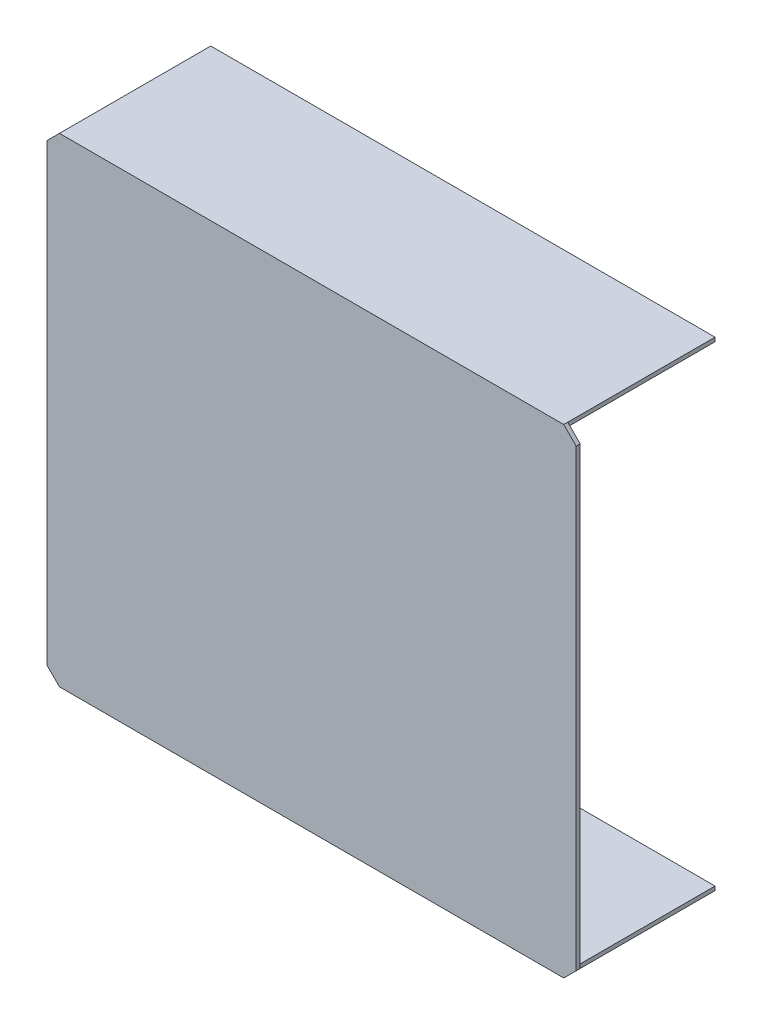
SolidWorks part; units mm, degrees
ref_plane "Front Plane" through (0, 0, 0) normal (0, 0, 1) x (1, 0, 0)
ref_plane "Top Plane" through (0, 0, 0) normal (0, 1, 0) x (1, 0, 0)
ref_plane "Right Plane" through (0, 0, 0) normal (1, 0, 0) x (0, 0, -1)
sketch "Sketch1" plane through (0, 0, 0) normal (0, 0, 1) x (1, 0, 0)
  line L0 (-101, -96) -> (101, -96)
  line L1 (101, -96) -> (106, -91)
  line L2 (106, -91) -> (106, 91)
  line L3 (106, 91) -> (101, 96)
  line L4 (101, 96) -> (-101, 96)
  line L5 (-101, 96) -> (-106, 91)
  line L6 (-106, 91) -> (-106, -91)
  line L7 (-106, -91) -> (-101, -96)
extrude "5052 sheet top panel" add sketch "Sketch1" along normal blind 1.6 from offset 86
sketch "Sketch2" plane through (0, 0, 0) normal (0, 0, 1) x (1, 0, 0)
  line L0 (-101, 94.4) -> (101, 94.4)
  line L1 (101, 94.4) -> (101, 96)
  line L2 (101, 96) -> (-101, 96)
  line L3 (-101, 96) -> (-101, 94.4)
  line L4 (-101, -96) -> (101, -96)
  line L5 (101, -96) -> (101, -94.4)
  line L6 (101, -94.4) -> (-101, -94.4)
  line L7 (-101, -94.4) -> (-101, -96)
extrude "Folded side skirts with open ends" add sketch "Sketch2" along normal blind 59 from offset 27
